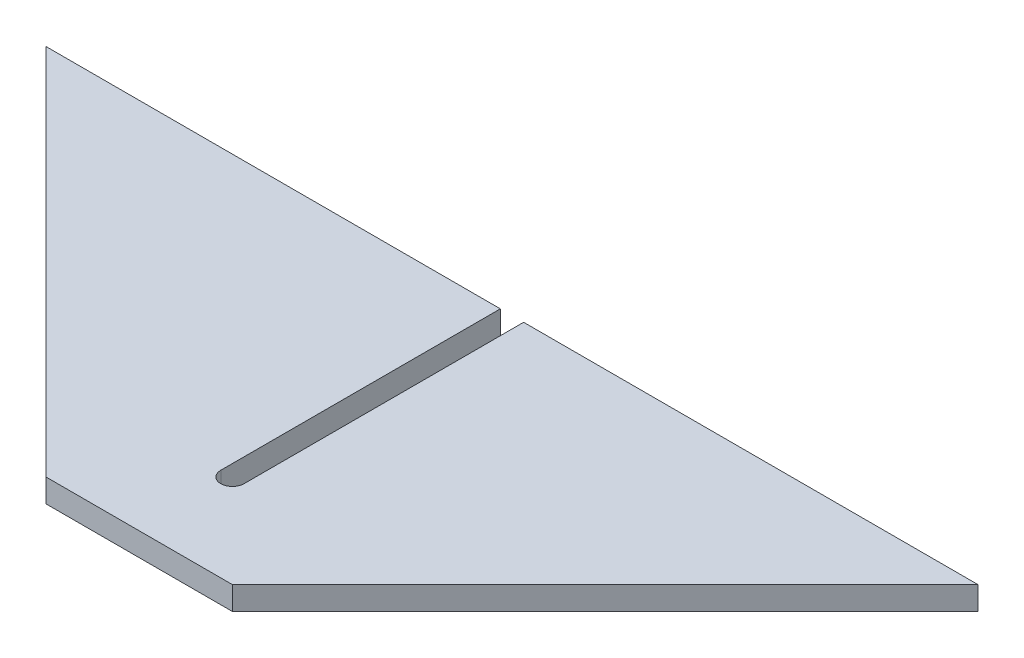
SolidWorks part; units mm, degrees
ref_plane "Front Plane" through (0, 0, 0) normal (0, 0, 1) x (1, 0, 0)
ref_plane "Top Plane" through (0, 0, 0) normal (0, 1, 0) x (1, 0, 0)
ref_plane "Right Plane" through (0, 0, 0) normal (1, 0, 0) x (0, 0, -1)
sketch "Sketch1" plane through (0, 0, 0) normal (0, 1, 0) x (1, 0, 0)
  line L0 (-25.4, -50.8) -> (-127, 50.8)
  line L1 (-25.4, -50.8) -> (25.4, -50.8)
  line L2 (-25.4, -50.8) -> (-25.4, 50.8)
  line L3 (-25.4, 50.8) -> (25.4, 50.8)
  line L4 (25.4, -50.8) -> (25.4, 50.8)
  line L5 (-25.4, -50.8) -> (25.4, 50.8) construction
  line L6 (-25.4, 50.8) -> (25.4, -50.8) construction
  line L7 (-127, 50.8) -> (-25.4, 50.8)
  line L8 (25.4, -50.8) -> (127, 50.8)
  line L9 (127, 50.8) -> (25.4, 50.8)
  line L10 (0, 50.8) -> (0, -25.4) construction
  line L13 (3.175, 50.8) -> (3.175, -25.4)
  line L14 (-3.175, 50.8) -> (-3.175, -25.4)
  arc A2 (3.175, 50.8) -> (-3.175, 50.8) centre (0, 50.8) ccw
  arc A3 (-3.175, -25.4) -> (3.175, -25.4) centre (0, -25.4) ccw
  point P0 (0, 0)
  point P10 (0, 12.7)
  dimension "D1" = 50.8
  dimension "D2" = 101.6
  dimension "D3" = 101.6
  dimension "D4" = 101.6
extrude "Boss-Extrude1" add sketch "Sketch1" along normal blind 6.35 contours L7 L0 L2 | A3 L14 L3 L2 L1 L4 L13 | L8 L9 L4
